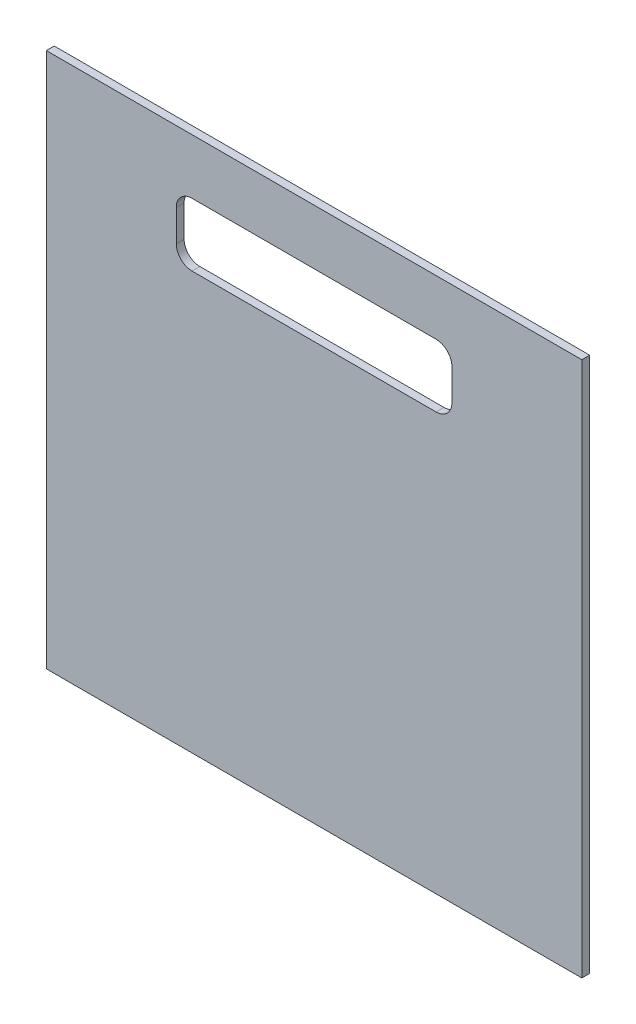
SolidWorks part; units mm, degrees
ref_plane "前视基准面" through (0, 0, 0) normal (0, 0, 1) x (1, 0, 0)
ref_plane "上视基准面" through (0, 0, 0) normal (0, 1, 0) x (1, 0, 0)
ref_plane "右视基准面" through (0, 0, 0) normal (1, 0, 0) x (0, 0, -1)
other "Configuration Table"
sketch "草图1" plane through (0, 0, 0) normal (0, 0, 1) x (1, 0, 0)
  line L1 (-34, -34) -> (34, -34)
  line L2 (-34, -34) -> (-34, 34)
  line L3 (-34, 34) -> (34, 34)
  line L4 (34, -34) -> (34, 34)
  line L5 (-34, -34) -> (34, 34) construction
  line L6 (-34, 34) -> (34, -34) construction
  line L7 (15.5, 19) -> (-15.5, 19)
  line L8 (17.5, 21) -> (17.5, 25)
  line L9 (15.5, 27) -> (-15.5, 27)
  line L10 (-17.5, 21) -> (-17.5, 25)
  line L11 (17.5, 19) -> (-17.5, 27) construction
  line L12 (17.5, 27) -> (-17.5, 19) construction
  arc A0 (17.5, 21) -> (15.5, 19) centre (15.5, 21) cw
  arc A1 (17.5, 25) -> (15.5, 27) centre (15.5, 25) ccw
  arc A2 (-17.5, 21) -> (-15.5, 19) centre (-15.5, 21) ccw
  arc A3 (-17.5, 25) -> (-15.5, 27) centre (-15.5, 25) cw
  point P0 (0, 0)
  point P6 (0, 23)
  dimension "D7" = 2
  dimension "D1" = 68
  dimension "D2" = 68
  dimension "D3" = 35
  dimension "D4" = 0
  dimension "D5" = 8
  dimension "D6" = 15
extrude "凸台-拉伸1" add sketch "草图1" along normal blind 1
